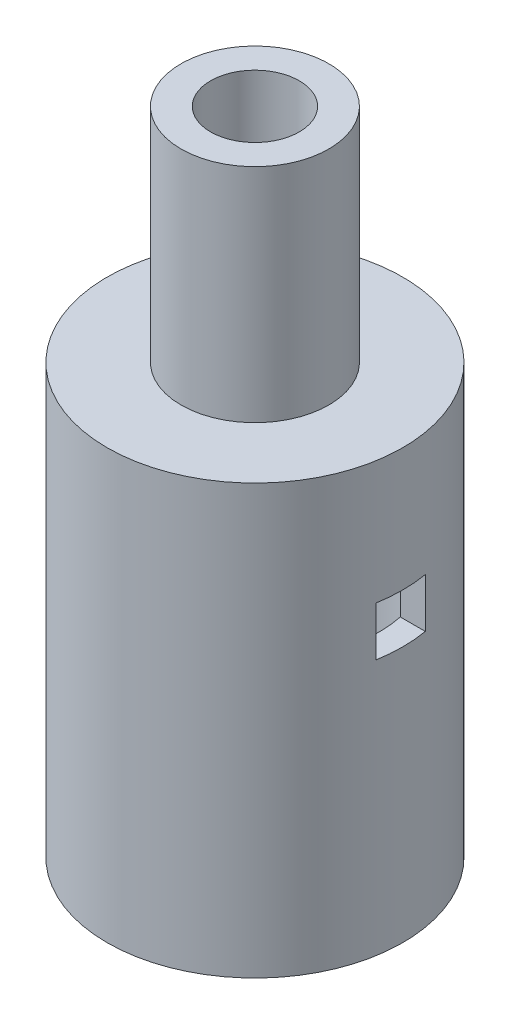
SolidWorks part; units mm, degrees
ref_plane "Front Plane" through (0, 0, 0) normal (0, 0, 1) x (1, 0, 0)
ref_plane "Top Plane" through (0, 0, 0) normal (0, 1, 0) x (1, 0, 0)
ref_plane "Right Plane" through (0, 0, 0) normal (1, 0, 0) x (0, 0, -1)
sketch "Sketch2" plane through (0, 0, 0) normal (0, 1, 0) x (1, 0, 0)
  circle A0 centre (0, 0) radius 7.62
  dimension "D1" = 15.24
extrude "Boss-Extrude1" add sketch "Sketch2" against normal blind 22.098 contours A0
sketch "Sketch3" plane through (0, -22.098, 0) normal (0, -1, 0) x (1, 0, 0)
  circle A0 centre (0, 0) radius 6.35
  dimension "D1" = 12.7
extrude "Cut-Extrude1" cut sketch "Sketch3" against normal blind 16.764
sketch "Sketch5" plane through (0, 0, 0) normal (0, 1, 0) x (1, 0, 0)
  circle A0 centre (0, 0) radius 2.3495
  dimension "D1" = 4.699
extrude "Cut-Extrude3" cut sketch "Sketch5" along normal blind 16.764 and the other way through all contours A0
sketch "Sketch6" plane through (0, 0, 0) normal (0, 1, 0) x (1, 0, 0)
  circle A0 centre (0, 0) radius 3.81
  dimension "D1" = 7.62
extrude "Boss-Extrude2" add sketch "Sketch6" along normal blind 11.43 contours A0
sketch "Sketch8" plane through (0, 11.43, 0) normal (0, 1, 0) x (1, 0, 0)
  circle A0 centre (0, 0) radius 2.286
  dimension "D1" = 4.572
extrude "Cut-Extrude4" cut sketch "Sketch8" against normal blind 11.176 contours A0
sketch "Sketch10" plane through (0, 0, 0) normal (0, -1, 0) x (1, 0, 0)
  circle A0 centre (0, 0) radius 1.7198
extrude "Cut-Extrude8" cut sketch "Sketch10" against normal up to next
sketch "Sketch12" plane through (0, 0, 0) normal (1, 0, 0) x (0, 0, -1)
  line L0 (7.62, 0) -> (-7.62, 0) construction
  line L1 (-1.27, -6.35) -> (1.27, -6.35)
  line L2 (-1.27, -6.35) -> (-1.27, -8.89)
  line L3 (-1.27, -8.89) -> (1.27, -8.89)
  line L4 (1.27, -6.35) -> (1.27, -8.89)
  line L5 (-1.27, -6.35) -> (1.27, -8.89) construction
  line L6 (-1.27, -8.89) -> (1.27, -6.35) construction
  point P0 (0, -7.62)
  dimension "D1" = 2.54
  dimension "D2" = 2.54
  dimension "D3" = 7.62
extrude "Cut-Extrude10" cut sketch "Sketch12" against normal through all both and the other way through all
